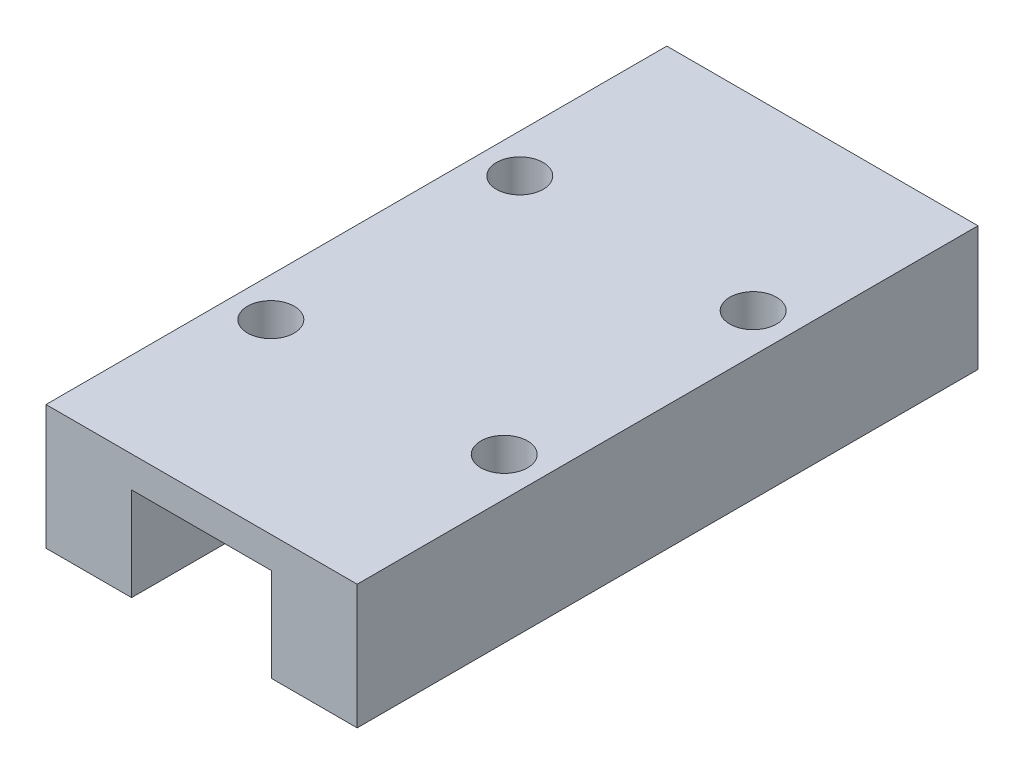
SolidWorks part; units mm, degrees
ref_plane "前视基准面" through (0, 0, 0) normal (0, 0, 1) x (1, 0, 0)
ref_plane "上视基准面" through (0, 0, 0) normal (0, 1, 0) x (1, 0, 0)
ref_plane "右视基准面" through (0, 0, 0) normal (1, 0, 0) x (0, 0, -1)
other "Configuration Table"
sketch "草图1" plane through (0, 0, 0) normal (0, 1, 0) x (1, 0, 0)
  line L0 (0, 0) -> (-3.7389, 0) construction
  line L1 (-10, 19.95) -> (10, 19.95)
  line L2 (-10, 19.95) -> (-10, -19.95)
  line L3 (-10, -19.95) -> (10, -19.95)
  line L4 (10, 19.95) -> (10, -19.95)
  line L5 (-10, 19.95) -> (10, -19.95) construction
  line L6 (-10, -19.95) -> (10, 19.95) construction
  line L7 (0, 0) -> (0, 6.0549) construction
  circle A0 centre (-7.5, 8) radius 1.5
  circle A1 centre (-7.5, -8) radius 1.5
  circle A2 centre (7.5, -8) radius 1.5
  circle A3 centre (7.5, 8) radius 1.5
  point P0 (0, 0)
  dimension "D3" = 3
  dimension "D1" = 20
  dimension "D2" = 39.9
  dimension "D4" = 7.5
  dimension "D5" = 8
extrude "凸台-拉伸1" add sketch "草图1" along normal blind 8
sketch "草图2" plane through (0, 0, 19.95) normal (0, 0, 1) x (1, 0, 0)
  line L5 (-10, 0) -> (10, 0) construction
  line L6 (-4.5, 0) -> (4.5, 0)
  line L7 (-4.5, 0) -> (-4.5, 6)
  line L8 (-4.5, 6) -> (4.5, 6)
  line L9 (4.5, 0) -> (4.5, 6)
  line L10 (0, 0) -> (0, 12) construction
  point P0 (0, 0)
  point P10 (0, 6)
  dimension "D1" = 9
  dimension "D2" = 6
extrude "切除-拉伸1" cut sketch "草图2" against normal blind 60
